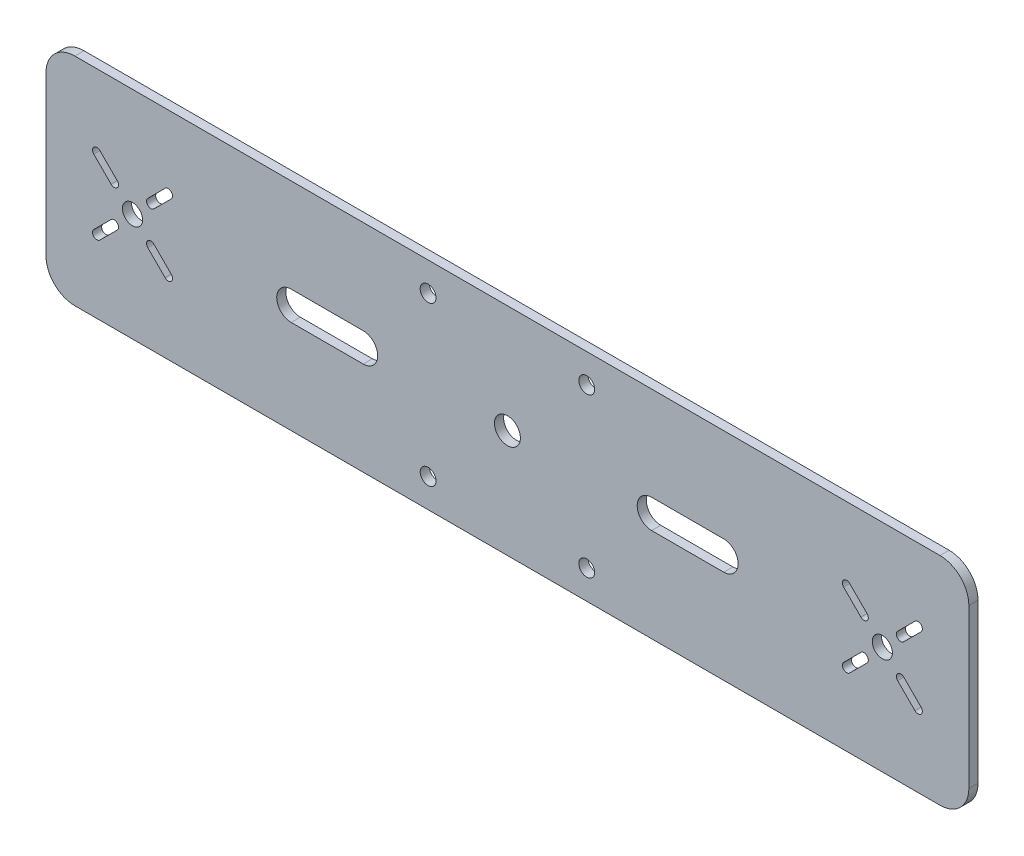
SolidWorks part; units mm, degrees
ref_plane "Front Plane" through (0, 0, 0) normal (0, 0, 1) x (1, 0, 0)
ref_plane "Top Plane" through (0, 0, 0) normal (0, 1, 0) x (1, 0, 0)
ref_plane "Right Plane" through (0, 0, 0) normal (1, 0, 0) x (0, 0, -1)
sketch "Sketch1" plane through (0, 0, 151.125) normal (0, 0, 1) x (1, 0, 0)
  line L0 (-130, 279.4) -> (130, 279.4) construction
  line L1 (-160, 316.9) -> (160, 316.9)
  line L2 (-160, 316.9) -> (-160, 241.9)
  line L3 (-160, 241.9) -> (160, 241.9)
  line L4 (160, 316.9) -> (160, 241.9)
  line L5 (-160, 316.9) -> (160, 241.9) construction
  line L6 (-160, 241.9) -> (160, 316.9) construction
  line L7 (130, 279.4) -> (160, 279.4) construction
  line L8 (-130, 279.4) -> (-160, 279.4) construction
  circle A0 centre (0, 279.4) radius 4.5 construction
  circle A1 centre (0, 279.4) radius 4.5
  circle A2 centre (130, 279.4) radius 114.3 construction
  circle A3 centre (-130, 279.4) radius 114.3 construction
  circle A4 centre (27.5, 251.9) radius 2.75 construction
  circle A5 centre (-27.5, 251.9) radius 2.75 construction
  circle A6 centre (-27.5, 306.9) radius 2.75 construction
  circle A7 centre (27.5, 306.9) radius 2.75 construction
  circle A8 centre (27.5, 251.9) radius 2.75
  circle A9 centre (-27.5, 251.9) radius 2.75
  circle A10 centre (-27.5, 306.9) radius 2.75
  circle A11 centre (27.5, 306.9) radius 2.75
  circle A12 centre (130, 279.4) radius 3.5
  circle A13 centre (-130, 279.4) radius 3.5
  dimension "D2" = 228.6
  dimension "D4" = 320
  dimension "D5" = 7
  dimension "D1" = 75
  dimension "D3" = 30
extrude "Boss-Extrude1" add sketch "Sketch1" along normal blind 3.175
sketch "Sketch2" plane through (0, 0, 154.3) normal (0, 0, 1) x (1, 0, 0)
  line L0 (-123.636, 285.764) -> (-117.6256, 291.7744) construction
  line L5 (-136.364, 273.036) -> (-123.636, 273.036) construction
  line L7 (-136.364, 273.036) -> (-136.364, 285.764) construction
  line L8 (-136.364, 285.764) -> (-123.636, 285.764) construction
  line L9 (-123.636, 273.036) -> (-123.636, 285.764) construction
  line L10 (-136.364, 273.036) -> (-123.636, 285.764) construction
  line L11 (-136.364, 285.764) -> (-123.636, 273.036) construction
  line L12 (-124.6967, 286.8246) -> (-118.6863, 292.835)
  line L13 (-122.5754, 284.7033) -> (-116.565, 290.7137)
  line L14 (-135.3033, 286.8246) -> (-141.3137, 292.835)
  line L15 (-137.4246, 284.7033) -> (-143.435, 290.7137)
  line L16 (-136.364, 285.764) -> (-142.3744, 291.7744) construction
  line L17 (-137.4246, 274.0967) -> (-143.435, 268.0863)
  line L18 (-135.3033, 271.9754) -> (-141.3137, 265.965)
  line L19 (-136.364, 273.036) -> (-142.3744, 267.0256) construction
  line L20 (-124.6967, 271.9754) -> (-118.6863, 265.965)
  line L21 (-122.5754, 274.0967) -> (-116.565, 268.0863)
  line L22 (-123.636, 273.036) -> (-117.6256, 267.0256) construction
  line L23 (0, 316.9) -> (0, 241.9) construction
  line L24 (160, 316.9) -> (-160, 316.9) construction
  line L25 (-160, 241.9) -> (160, 241.9) construction
  line L26 (0, 279.4) -> (-50, 279.4) construction
  line L27 (-50, 279.4) -> (-75, 279.4) construction
  line L28 (-50, 274.4) -> (-75, 274.4)
  line L29 (-50, 284.4) -> (-75, 284.4)
  circle A0 centre (-130, 279.4) radius 17.5 construction
  circle A1 centre (-130, 279.4) radius 9 construction
  arc A2 (-124.6967, 286.8246) -> (-122.5754, 284.7033) centre (-123.636, 285.764) ccw
  arc A3 (-116.565, 290.7137) -> (-118.6863, 292.835) centre (-117.6256, 291.7744) ccw
  arc A4 (-137.4246, 284.7033) -> (-135.3033, 286.8246) centre (-136.364, 285.764) ccw
  arc A5 (-141.3137, 292.835) -> (-143.435, 290.7137) centre (-142.3744, 291.7744) ccw
  arc A6 (-135.3033, 271.9754) -> (-137.4246, 274.0967) centre (-136.364, 273.036) ccw
  arc A7 (-143.435, 268.0863) -> (-141.3137, 265.965) centre (-142.3744, 267.0256) ccw
  arc A8 (-122.5754, 274.0967) -> (-124.6967, 271.9754) centre (-123.636, 273.036) ccw
  arc A9 (-118.6863, 265.965) -> (-116.565, 268.0863) centre (-117.6256, 267.0256) ccw
  arc A10 (-50, 274.4) -> (-50, 284.4) centre (-50, 279.4) ccw
  arc A11 (-75, 284.4) -> (-75, 274.4) centre (-75, 279.4) ccw
  point P8 (-120.6308, 288.7692)
  point P18 (-139.3692, 288.7692)
  point P25 (-139.3692, 270.0308)
  point P32 (-120.6308, 270.0308)
  point P38 (-130, 279.4)
  point P44 (-62.5, 279.4)
  dimension "D1" = 35
  dimension "D2" = 18
  dimension "D3" = 3
  dimension "D7" = 5
  dimension "D4" = 4
  dimension "D5" = 50
  dimension "D6" = 25
extrude "Mounting and Access Holes" cut sketch "Sketch2" against normal through all both and the other way through all
mirror "Mirror1" about plane through (0, 0, 0) normal (1, 0, 0) of "Mounting and Access Holes"
fillet "Fillet1" radius 10 4 edges at (-160, 316.9, 152.7125) (-160, 241.9, 152.7125) (160, 241.9, 152.7125) (160, 316.9, 152.7125)
